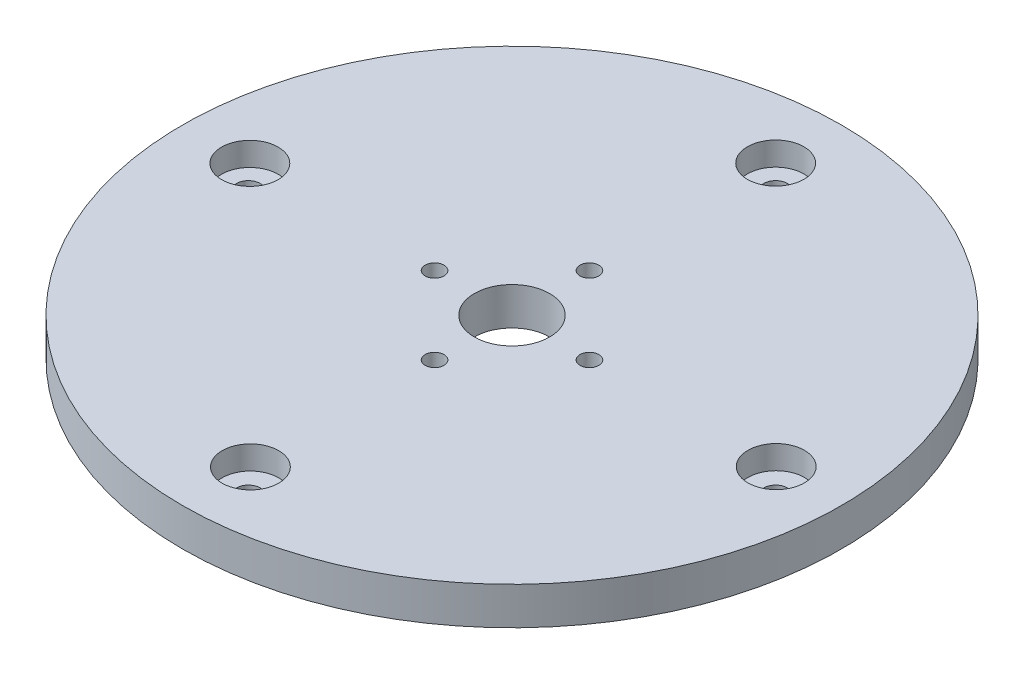
SolidWorks part; units mm, degrees
ref_plane "Front Plane" through (0, 0, 0) normal (0, 0, 1) x (1, 0, 0)
ref_plane "Top Plane" through (0, 0, 0) normal (0, 1, 0) x (1, 0, 0)
ref_plane "Right Plane" through (0, 0, 0) normal (1, 0, 0) x (0, 0, -1)
sketch "Sketch1" plane through (0, 0, 0) normal (0, 1, 0) x (1, 0, 0)
  circle A0 centre (0, 0) radius 35
  dimension "D1" = 70
extrude "Boss-Extrude1" add sketch "Sketch1" along normal blind 4 contours A0
sketch "Sketch2" plane through (0, 4, 0) normal (0, 1, 0) x (1, 0, 0)
  circle A2 centre (0, 8.2271) radius 1
  circle A3 centre (8.2271, 0) radius 1
  circle A4 centre (0, -8.2271) radius 1
  circle A5 centre (-8.2271, 0) radius 1
  circle A7 centre (0, -28) radius 1.25
  circle A8 centre (-28, 0) radius 1.25
  circle A9 centre (0, 28) radius 1.25
  circle A10 centre (28, 0) radius 1.25
  dimension "D2" = 4
  dimension "D3" = 4
extrude "Cut-Extrude1" cut sketch "Sketch2" against normal through all
sketch "Sketch3" plane through (0, 0, 0) normal (0, -1, 0) x (1, 0, 0)
  circle A0 centre (0, 0) radius 4
  dimension "D1" = 8
extrude "Cut-Extrude2" cut sketch "Sketch3" against normal up to next
sketch "Sketch4" plane through (0, 4, 0) normal (0, 1, 0) x (1, 0, 0)
  circle A0 centre (0, 28) radius 3
  circle A1 centre (27.9481, 0.1095) radius 3
  circle A2 centre (0.0576, -27.8386) radius 3
  circle A3 centre (-27.8905, 0.0519) radius 3
  dimension "D1" = 6
  dimension "D2" = 4
extrude "Cut-Extrude3" cut sketch "Sketch4" against normal blind 2.5
sketch "Sketch5" plane through (0, 0, 0) normal (0, -1, 0) x (1, 0, 0)
  circle A0 centre (0, 8.2271) radius 2
  circle A1 centre (8.2271, 0) radius 2
  circle A2 centre (0, -8.2271) radius 2
  circle A3 centre (-8.2271, 0) radius 2
  dimension "D1" = 4
  dimension "D2" = 4
extrude "Cut-Extrude4" cut sketch "Sketch5" against normal blind 2.5
